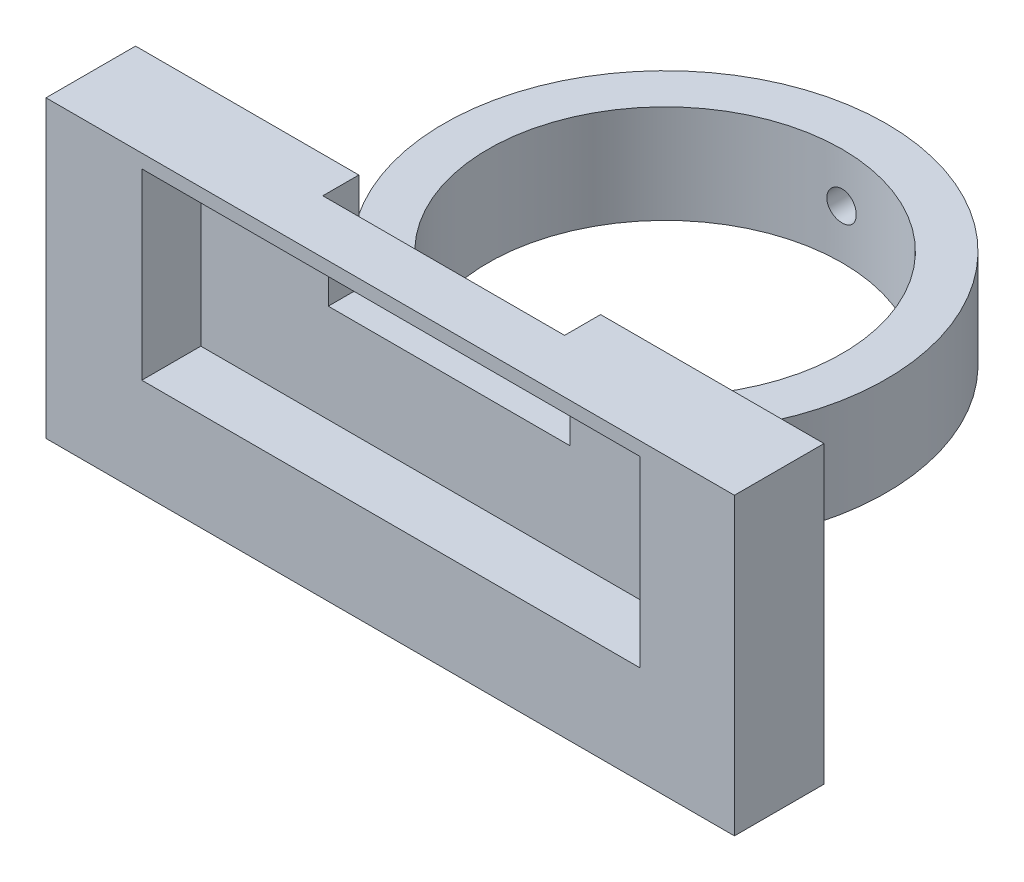
SolidWorks part; units mm, degrees
ref_plane "Alzado" through (0, 0, 0) normal (0, 0, 1) x (1, 0, 0)
ref_plane "Planta" through (0, 0, 0) normal (0, 1, 0) x (1, 0, 0)
ref_plane "Vista lateral" through (0, 0, 0) normal (1, 0, 0) x (0, 0, -1)
sketch "Croquis1" plane through (0, 0, 0) normal (0, 1, 0) x (1, 0, 0)
  circle A0 centre (0, 0) radius 18
  circle A1 centre (0, 0) radius 22.5
  dimension "D1" = 36
  dimension "D2" = 45
extrude "Saliente-Extruir1" add sketch "Croquis1" along normal blind 10
sketch "Croquis3" plane through (0, 10, 0) normal (0, 1, 0) x (1, 0, 0)
  line L0 (0, -7.9362) -> (0, -36.5672) construction
  line L1 (-35, -18.8446) -> (35, -18.8446)
  line L2 (-35, -18.8446) -> (-35, -27.951)
  line L3 (-35, -27.951) -> (35, -27.951)
  line L4 (35, -18.8446) -> (35, -27.951)
  dimension "D1" = 70
extrude "Saliente-Extruir2" add sketch "Croquis3" along normal blind 10 and the other way blind 20
sketch "Croquis5" plane through (0, 0, 0) normal (0, 0, 1) x (1, 0, 0)
  line L0 (-16.0971, 5) -> (22.3826, 5) construction
  line L1 (-35, -10) -> (35, -10) construction
  line L2 (-35, 20) -> (35, 20) construction
  circle A0 centre (0, 5) radius 1.5
  dimension "D1" = 3
extrude "Cortar-Extruir1" cut sketch "Croquis5" against normal through all
sketch "Croquis7" plane through (0, 0, 27.951) normal (0, 0, 1) x (1, 0, 0)
  line L1 (-25, 11.3531) -> (25, 11.3531)
  line L2 (-25, 11.3531) -> (-25, 0.8676)
  line L3 (-25, 0.8676) -> (25, 0.8676)
  line L4 (25, 11.3531) -> (25, 0.8676)
  line L5 (-30, 15) -> (-30, -5) construction
  line L6 (30, 15) -> (30, -5) construction
  point P5 (21.3539, -1.425)
  point P6 (-22.7624, 11.3531)
  point P7 (-30, 15)
  dimension "D1" = 5
  dimension "D2" = 5
extrude "Cortar-Extruir2" cut sketch "Croquis7" against normal blind 5
sketch "Croquis8" plane through (0, 20, 0) normal (0, 1, 0) x (1, 0, 0)
  line L0 (-35, -27.951) -> (35, -27.951) construction
  line L1 (-25.257, -27.951) -> (25.3733, -27.951)
  line L2 (-25.257, -27.951) -> (-25.257, -21.951)
  line L3 (-25.257, -21.951) -> (25.3733, -21.951)
  line L4 (25.3733, -27.951) -> (25.3733, -21.951)
  dimension "D1" = 6
extrude "Cortar-Extruir3" cut sketch "Croquis8" against normal blind 20
sketch "Croquis11" plane through (0, 0, 18.8446) normal (0, 0, -1) x (-1, 0, 0)
  line L1 (-12.2936, 10) -> (12.2981, 10)
  line L2 (-12.2936, 10) -> (-12.2936, 18.2213)
  line L3 (-12.2936, 18.2213) -> (12.2981, 18.2213)
  line L4 (12.2981, 10) -> (12.2981, 18.2213)
extrude "Cortar-Extruir4" cut sketch "Croquis11" against normal blind 16
sketch "Croquis12" plane through (25.3733, 0, 0) normal (-1, 0, 0) x (0, 0, 1)
  line L0 (27.951, -10) -> (27.951, 20) construction
  line L1 (21.951, 20) -> (27.951, 20)
  line L2 (21.951, 20) -> (21.951, 18.6139)
  line L3 (21.951, 18.6139) -> (27.951, 18.6139)
  line L4 (27.951, 20) -> (27.951, 18.6139)
extrude "Saliente-Extruir3" add sketch "Croquis12" along normal blind 56
sketch "Croquis13" plane through (0, 20, 0) normal (0, 1, 0) x (1, 0, 0)
  line L1 (-12.2981, -18.8446) -> (12.2857, -18.8446)
  line L2 (-12.2981, -18.8446) -> (-12.2981, -22.5068)
  line L3 (-12.2981, -22.5068) -> (12.2857, -22.5068)
  line L4 (12.2857, -18.8446) -> (12.2857, -22.5068)
extrude "Cortar-Extruir5" cut sketch "Croquis13" against normal blind 5
